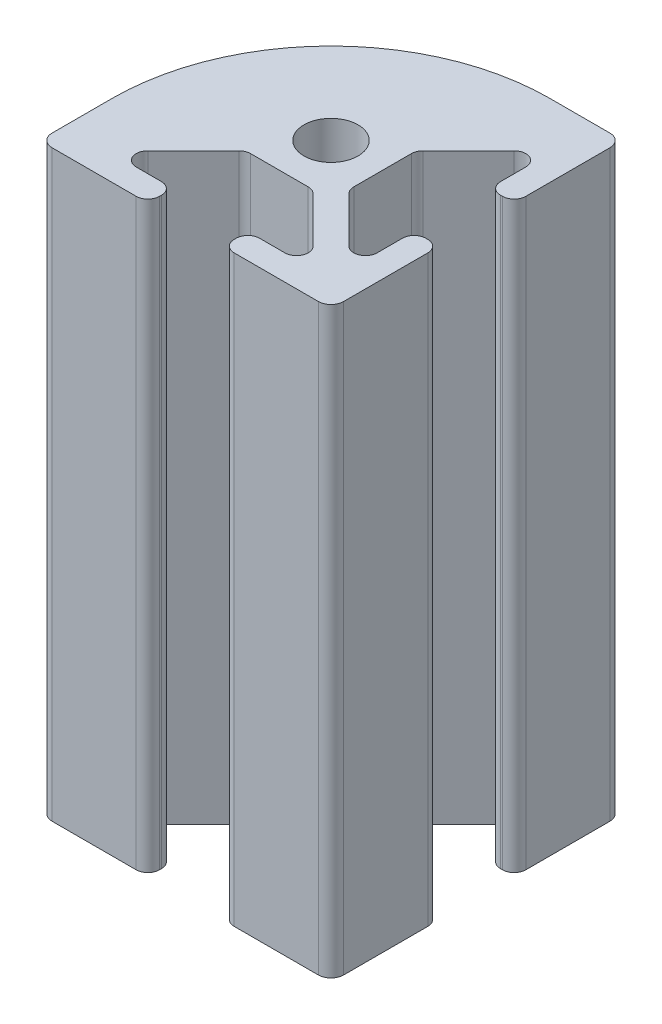
SolidWorks part; units mm, degrees
ref_plane "Front" through (0, 0, 0) normal (0, 0, 1) x (1, 0, 0)
ref_plane "Top" through (0, 0, 0) normal (0, 1, 0) x (1, 0, 0)
ref_plane "Right" through (0, 0, 0) normal (1, 0, 0) x (0, 0, -1)
sketch "Sketch1" plane through (0, 0, 0) normal (0, 0, 1) x (1, 0, 0)
  line L0 (0, 0) -> (0, 50.8)
  dimension "D1" = 50.8
other "10 1012-S(1)"
ref_plane "Plane1" through (0, 0, 0) normal (0, 1, 0) x (-1, 0, 0)
sketch "Sketch11" plane through (0, 0, 0) normal (0, 1, 0) x (-1, 0, 0)
  line L0 (24.2951, 0) -> (16.9672, 0)
  line L1 (0, -1.1049) -> (0, -24.2951) construction
  line L2 (15.9512, -1.016) -> (15.9512, -1.1938)
  line L3 (16.9672, -2.2098) -> (19.1748, -2.2098)
  line L4 (19.8932, -3.9442) -> (15.9308, -7.9066)
  line L5 (15.2124, -8.2042) -> (10.1876, -8.2042)
  line L6 (9.4692, -7.9066) -> (5.5068, -3.9442)
  line L7 (6.2252, -2.2098) -> (8.4328, -2.2098)
  line L8 (9.4488, -1.1938) -> (9.4488, -1.016)
  line L9 (25.4, -6.35) -> (25.4, -1.1049)
  line L10 (6.35, -25.4) -> (1.1049, -25.4)
  line L11 (0, -12.7) -> (12.7, -12.7) construction
  line L12 (12.7, -12.7) -> (12.7, 0) construction
  line L13 (15.9512, -2.2098) -> (12.7, 0) construction
  line L14 (12.7, 0) -> (9.4488, -2.2098) construction
  line L15 (12.7, -12.7) -> (25.4, 0) construction
  line L16 (8.4328, 0) -> (1.1049, 0)
  line L17 (15.9512, 0) -> (12.7, 0) construction
  line L18 (12.7, 0) -> (9.4488, 0) construction
  line L19 (0, -1.1049) -> (0, -8.4328)
  line L20 (1.016, -9.4488) -> (1.1938, -9.4488)
  line L21 (2.2098, -8.4328) -> (2.2098, -6.2252)
  line L22 (3.9442, -5.5068) -> (7.9066, -9.4692)
  line L23 (8.2042, -10.1876) -> (8.2042, -15.2124)
  line L24 (7.9066, -15.9308) -> (3.9442, -19.8932)
  line L25 (2.2098, -19.1748) -> (2.2098, -16.9672)
  line L26 (1.1938, -15.9512) -> (1.016, -15.9512)
  line L27 (0, -16.9672) -> (0, -24.2951) construction
  line L28 (0, -16.9672) -> (0, -24.2951)
  arc A0 (25.4, -6.35) -> (6.35, -25.4) centre (6.35, -6.35) cw
  arc A1 (16.9672, -2.2098) -> (15.9512, -1.1938) centre (16.9672, -1.1938) cw
  arc A2 (16.9672, 0) -> (15.9512, -1.016) centre (16.9672, -1.016) ccw
  arc A3 (8.4328, 0) -> (9.4488, -1.016) centre (8.4328, -1.016) cw
  arc A4 (9.4488, -1.1938) -> (8.4328, -2.2098) centre (8.4328, -1.1938) cw
  arc A5 (5.5068, -3.9442) -> (6.2252, -2.2098) centre (6.2252, -3.2258) cw
  arc A6 (10.1876, -8.2042) -> (9.4692, -7.9066) centre (10.1876, -7.1882) cw
  arc A7 (15.9308, -7.9066) -> (15.2124, -8.2042) centre (15.2124, -7.1882) cw
  arc A8 (19.8932, -3.9442) -> (19.1748, -2.2098) centre (19.1748, -3.2258) ccw
  arc A9 (25.4, -1.1049) -> (24.2951, 0) centre (24.2951, -1.1049) ccw
  arc A10 (1.1049, -25.4) -> (0, -24.2951) centre (1.1049, -24.2951) cw construction
  arc A11 (1.1049, 0) -> (0, -1.1049) centre (1.1049, -1.1049) ccw
  arc A12 (0, -8.4328) -> (1.016, -9.4488) centre (1.016, -8.4328) ccw
  arc A13 (2.2098, -8.4328) -> (1.1938, -9.4488) centre (1.1938, -8.4328) cw
  arc A14 (3.9442, -5.5068) -> (2.2098, -6.2252) centre (3.2258, -6.2252) ccw
  arc A15 (7.9066, -9.4692) -> (8.2042, -10.1876) centre (7.1882, -10.1876) cw
  arc A16 (8.2042, -15.2124) -> (7.9066, -15.9308) centre (7.1882, -15.2124) cw
  arc A17 (3.9442, -19.8932) -> (2.2098, -19.1748) centre (3.2258, -19.1748) cw
  arc A18 (1.1938, -15.9512) -> (2.2098, -16.9672) centre (1.1938, -16.9672) cw
  arc A19 (0, -16.9672) -> (1.016, -15.9512) centre (1.016, -16.9672) cw
  circle A20 centre (12.7, -12.7) radius 2.3546
  arc A21 (1.1049, -25.4) -> (0, -24.2951) centre (1.1049, -24.2951) cw
  point P43 (0, -25.4)
  point P46 (0, 0)
  point P47 (0, 0)
  point P74 (12.7, -12.7)
  dimension "D1" = 25.4
  dimension "D7" = 19.05
  dimension "D10" = 1.016
  dimension "D11" = 1.1049
  dimension "D12" = 1.1049
  dimension "D13" = 1.1049
  dimension "D15" = 4.7091
  dimension "D2" = 6.5024
  dimension "D3" = 8.2042
  dimension "D4" = 2.2098
  dimension "D5" = 45
  dimension "D6" = 2.2098
  dimension "D8" = 12.7
  dimension "D9" = 25.4
  dimension "D14" = 2
